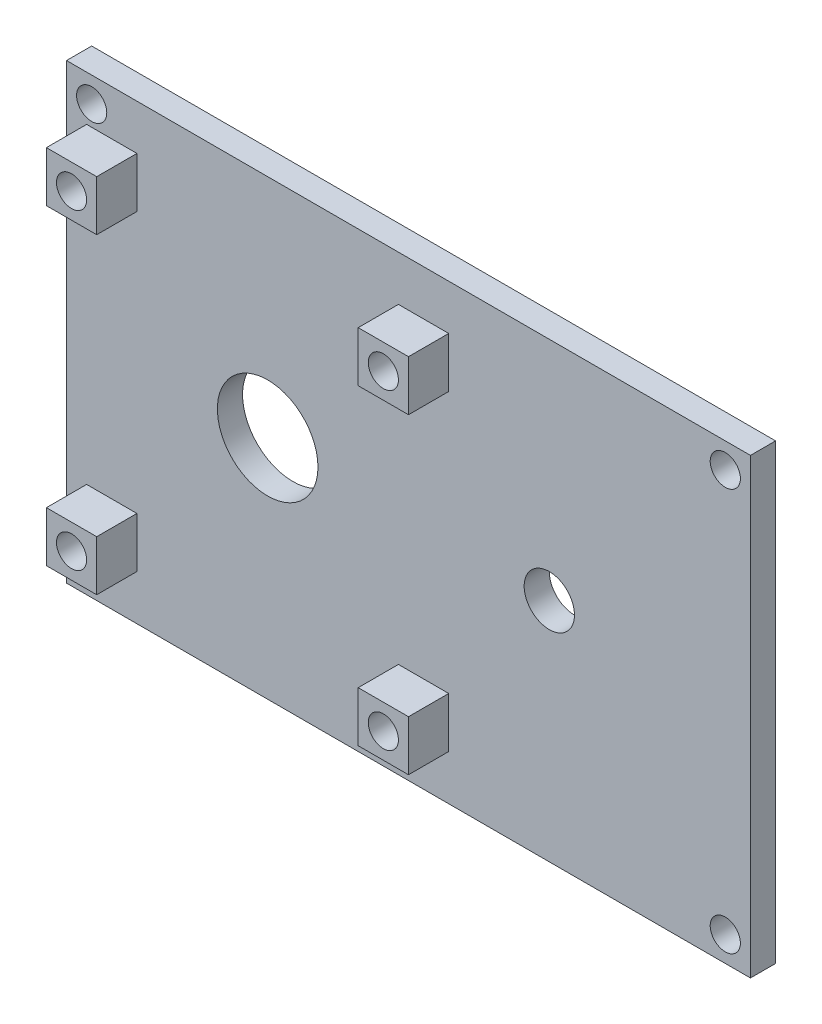
SolidWorks part; units mm, degrees
ref_plane "Přední rovina" through (0, 0, 0) normal (0, 0, 1) x (1, 0, 0)
ref_plane "Horní rovina" through (0, 0, 0) normal (0, 1, 0) x (1, 0, 0)
ref_plane "Pravá rovina" through (0, 0, 0) normal (1, 0, 0) x (0, 0, -1)
sketch "Skica1" plane through (0, 0, 0) normal (0, 0, 1) x (1, 0, 0)
  line L1 (-34, -22.5) -> (34, -22.5)
  line L2 (-34, -22.5) -> (-34, 22.5)
  line L3 (-34, 22.5) -> (34, 22.5)
  line L4 (34, -22.5) -> (34, 22.5)
  line L5 (-34, -22.5) -> (34, 22.5) construction
  line L6 (-34, 22.5) -> (34, -22.5) construction
  line L7 (-34, 22.5) -> (-23.5, 22.5)
  line L8 (-34, 22.5) -> (-34, 10.5)
  circle A0 centre (-31.5, 20) radius 1.5
  circle A1 centre (31.5, 20) radius 1.5
  circle A2 centre (31.5, -20) radius 1.5
  circle A3 centre (-31.5, -20) radius 1.5
  circle A4 centre (-14, 0) radius 5
  circle A5 centre (14, 0) radius 2.5
  point P0 (0, 0)
  point P20 (-34, 0)
  dimension "D5" = 3
  dimension "D6" = 3
  dimension "D9" = 3
  dimension "D12" = 3
  dimension "D15" = 10
  dimension "D17" = 5
  dimension "D1" = 45
  dimension "D2" = 68
  dimension "D3" = 2.5
  dimension "D4" = 2.5
  dimension "D7" = 2.5
  dimension "D8" = 2.5
  dimension "D10" = 2.5
  dimension "D11" = 2.5
  dimension "D13" = 2.5
  dimension "D14" = 2.5
  dimension "D16" = 20
  dimension "D18" = 28
extrude "Přidat vysunutím1" add sketch "Skica1" along normal blind 2.5 contours L1 L4 L3 L2 A3 A2 A1 A0
sketch "Skica2" plane through (0, 0, 2.5) normal (0, 0, 1) x (1, 0, 0)
  line L0 (-29.5, -15.5) -> (1.5, 15.5) construction
  line L1 (-29.5, 15.5) -> (1.5, -15.5) construction
  line L3 (-32, 18) -> (-27, 18)
  line L4 (-32, 18) -> (-32, 13)
  line L5 (-32, 13) -> (-27, 13)
  line L6 (-27, 18) -> (-27, 13)
  line L7 (-32, 18) -> (-27, 13) construction
  line L8 (-32, 13) -> (-27, 18) construction
  line L9 (-1, 18) -> (4, 18)
  line L10 (-1, 18) -> (-1, 13)
  line L11 (-1, 13) -> (4, 13)
  line L12 (4, 18) -> (4, 13)
  line L13 (-1, 18) -> (4, 13) construction
  line L14 (-1, 13) -> (4, 18) construction
  line L15 (-1, -13) -> (4, -13)
  line L16 (-1, -13) -> (-1, -18)
  line L17 (-1, -18) -> (4, -18)
  line L18 (4, -13) -> (4, -18)
  line L19 (-1, -13) -> (4, -18) construction
  line L20 (-1, -18) -> (4, -13) construction
  line L21 (-32, -13) -> (-27, -13)
  line L22 (-32, -13) -> (-32, -18)
  line L23 (-32, -18) -> (-27, -18)
  line L24 (-27, -13) -> (-27, -18)
  line L25 (-32, -13) -> (-27, -18) construction
  line L26 (-32, -18) -> (-27, -13) construction
  circle A0 centre (-29.5, 15.5) radius 1.5
  circle A1 centre (1.5, 15.5) radius 1.5
  circle A2 centre (1.5, -15.5) radius 1.5
  circle A3 centre (-29.5, -15.5) radius 1.5
  circle A5 centre (-14, 0) radius 5 construction
  circle A6 centre (-14, 0) radius 5 construction
  point P14 (-14, 0)
  dimension "D1" = 3
  dimension "D2" = 31
  dimension "D3" = 31
  dimension "D4" = 5
  dimension "D5" = 5
  dimension "D6" = 5
  dimension "D7" = 5
  dimension "D8" = 5
  dimension "D9" = 5
  dimension "D10" = 5
extrude "Přidat vysunutím2" add sketch "Skica2" along normal blind 4
sketch "Skica5" plane through (0, 0, 2.5) normal (0, 0, 1) x (1, 0, 0)
  circle A0 centre (-29.5, 15.5) radius 1.5
  circle A1 centre (-29.5, 15.5) radius 1.5 construction
  circle A2 centre (1.5, 15.5) radius 1.5
  circle A3 centre (1.5, 15.5) radius 1.5 construction
  circle A4 centre (1.5, -15.5) radius 1.5
  circle A5 centre (1.5, -15.5) radius 1.5 construction
  circle A6 centre (-29.5, -15.5) radius 1.5
  circle A7 centre (-29.5, -15.5) radius 1.5 construction
extrude "Odebrat vysunutím1" cut sketch "Skica5" against normal blind 2.5
chamfer "Zkosení1" distance 1.5 angle 45 4 edges at (3, -15.5, 0) (-28, -15.5, 0) (-28, 15.5, 0) (3, 15.5, 0)
